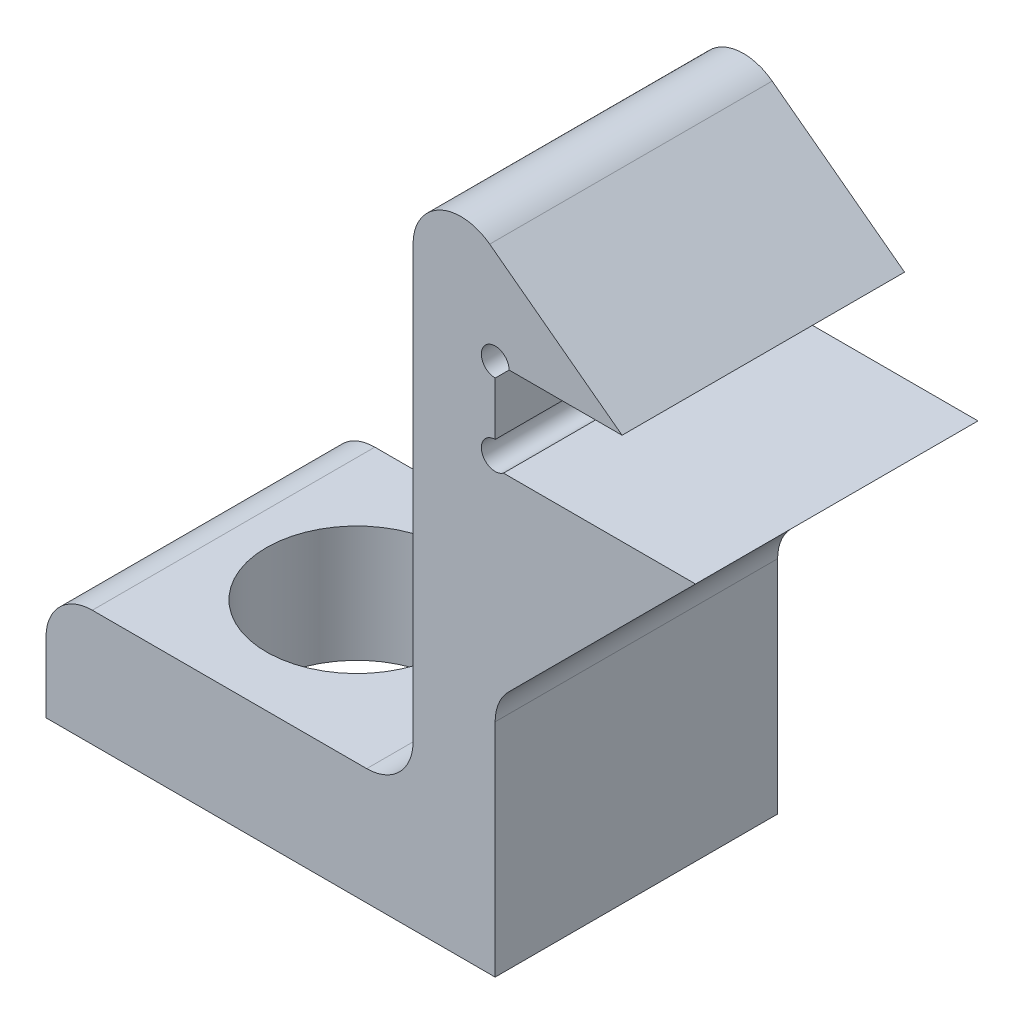
SolidWorks part; units mm, degrees
ref_plane "Front Plane" through (0, 0, 0) normal (0, 0, 1) x (1, 0, 0)
ref_plane "Top Plane" through (0, 0, 0) normal (0, 1, 0) x (1, 0, 0)
ref_plane "Right Plane" through (0, 0, 0) normal (1, 0, 0) x (0, 0, -1)
sketch "Sketch3" plane through (0, 0, 0) normal (0, 0, 1) x (1, 0, 0)
  line L0 (-1.453, 2.8796) -> (-1.453, 10.5097)
  line L1 (-0.0963, 11.188) -> (2.2469, 9.43)
  line L2 (2.2469, 9.43) -> (0.2469, 9.43)
  line L3 (0.0013, 9.1844) -> (0.0013, 8.2428)
  line L4 (0.1477, 7.8) -> (3.547, 7.8)
  line L5 (3.547, 7.8) -> (0.2398, 4.4928)
  line L10 (-2.273, 2.0596) -> (-7.13, 2.0596)
  line L11 (-7.95, 1.2396) -> (-7.95, 0)
  line L12 (-7.95, 0) -> (0, 0)
  line L13 (0, 3.9139) -> (0, 0)
  arc A0 (-1.453, 10.5097) -> (-0.0963, 11.188) centre (-0.6051, 10.5097) cw
  arc A1 (0.2469, 9.43) -> (0.0013, 9.1844) centre (0.0013, 9.43) ccw
  arc A2 (0.0013, 8.2428) -> (0.1477, 7.8) centre (0.0013, 7.9972) ccw
  arc A3 (0.2398, 4.4928) -> (0, 3.9139) centre (0.8187, 3.9139) ccw
  arc A6 (-7.95, 1.2396) -> (-7.13, 2.0596) centre (-7.13, 1.2396) cw
  arc A7 (-1.453, 2.8796) -> (-2.273, 2.0596) centre (-2.273, 2.8796) cw
  point P0 (1.8473, 7.8)
  dimension "D2" = 0.82
  dimension "D3" = 0.82
  dimension "D1" = 0.8479
  dimension "D4" = 0.2456
  dimension "D9" = 0.8187
  dimension "D5" = 1.63
  dimension "D6" = 7.95
  dimension "D7" = 2.0596
  dimension "D10" = 0.9415
  dimension "D11" = 1.4543
  dimension "D12" = 5
  dimension "D13" = 1.0797
  dimension "D14" = 2
  dimension "D15" = 1.4328
  dimension "D16" = 135
  dimension "D17" = 7.8
extrude "Boss-Extrude1" add sketch "Sketch3" along normal mid plane 5
sketch "Sketch4" plane through (0, 2.0596, 0) normal (0, 1, 0) x (1, 0, 0)
  line L0 (-7.95, -2.5) -> (-7.95, 2.5) construction
  circle A0 centre (-4.95, 0) radius 1.6
  dimension "D1" = 3.2
  dimension "D2" = 3
extrude "Cut-Extrude1" cut sketch "Sketch4" against normal through all
